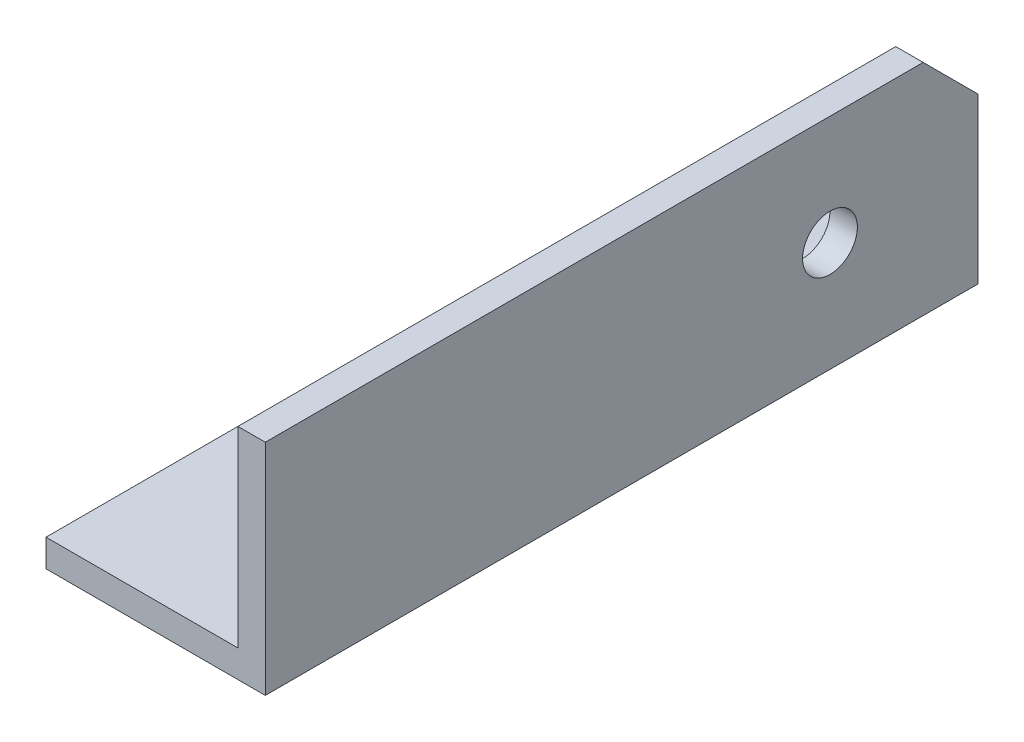
SolidWorks part; units mm, degrees
ref_plane "Front" through (0, 0, 0) normal (0, 0, 1) x (1, 0, 0)
ref_plane "Top" through (0, 0, 0) normal (0, 1, 0) x (1, 0, 0)
ref_plane "Right" through (0, 0, 0) normal (1, 0, 0) x (0, 0, -1)
sketch "Sketch2" plane through (0, 0, 0) normal (0, 0, 1) x (1, 0, 0)
  line L0 (-40, 0) -> (0, 0)
  line L1 (0, 0) -> (0, 40)
  dimension "D1" = 40
  dimension "D2" = 40
extrude "Extrude-Thin1" add sketch "Sketch2" along normal blind 65 and the other way blind 65 thin thin type one direction reverse wall 5
chamfer "Chamfer1" distance 10 angle 45 2 edges at (-40, 2.5, -65) (-2.5, 40, -65)
sketch "Sketch3" plane through (-5, 0, 0) normal (-1, 0, 0) x (0, 0, 1)
  line L0 (-55, 40) -> (65, 40) construction
  line L1 (-65, 5) -> (-65, 30) construction
  circle A0 centre (-38, 20) radius 5
  dimension "D1" = 10
  dimension "D2" = 20
  dimension "D3" = 27
extrude "Cut-Extrude1" cut sketch "Sketch3" against normal blind 10
